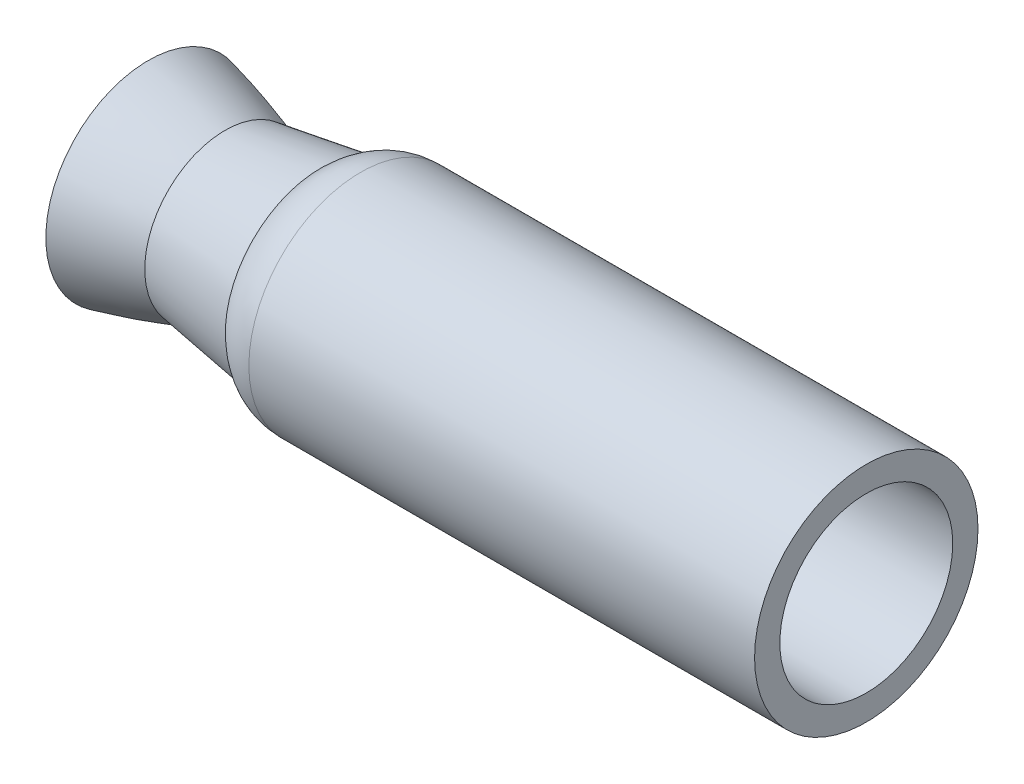
SolidWorks part; units mm, degrees
material "Thornel Mat VMA"
ref_plane "Front Plane" through (0, 0, 0) normal (0, 0, 1) x (1, 0, 0)
ref_plane "Top Plane" through (0, 0, 0) normal (0, 1, 0) x (1, 0, 0)
ref_plane "Right Plane" through (0, 0, 0) normal (1, 0, 0) x (0, 0, -1)
sketch "Sketch1" plane through (0, 0, 0) normal (0, 0, 1) x (1, 0, 0)
  line L0 (189.133, 27.386) -> (28.9492, 27.386)
  line L1 (21.8782, 24.4571) -> (13.5417, 16.1206)
  line L3 (0, 0) -> (-234.9488, 0) construction
  line L5 (16.2213, 30.1139) -> (-13.9816, 25.4377)
  line L8 (189.133, 35.386) -> (28.9492, 35.386)
  line L12 (16.2213, 30.1139) -> (7.8848, 21.7775)
  line L13 (189.133, 27.386) -> (189.133, 35.386)
  line L14 (-40.127, 24.64) -> (-38.315, 32.4321)
  arc A0 (28.9492, 27.386) -> (21.8782, 24.4571) centre (28.9492, 17.386) ccw
  arc A4 (28.9492, 35.386) -> (16.2213, 30.1139) centre (28.9492, 17.386) ccw
  arc A7 (2.3482, 19.2268) -> (2.3482, 19.2268) centre (2.3482, 19.2268) cw
  arc A8 (7.8848, 21.7775) -> (2.3482, 19.2268) centre (1.6623, 28) cw construction
  arc A9 (2.3482, 19.2268) -> (7.8848, 21.7775) centre (1.6623, 28) ccw
  arc A10 (0.1069, 11.2722) -> (0, 11.5361) centre (3.1693, 12.6659) cw construction
  arc A11 (13.5417, 16.1206) -> (0.1069, 11.2722) centre (1.6623, 28) cw construction
  arc A12 (13.5417, 16.1206) -> (1.6623, 11.2) centre (1.6623, 28) cw
  arc A13 (1.6623, 11.2) -> (0, 11.5361) centre (1.6623, 15.4784) cw
  spline S0 degree 2 poles (0, 11.5361) (-19.9483, 19.9476) (-40.127, 24.64) knots 0 0 0 1 1 1 construction
  spline S1 degree 1 poles (2.3482, 19.2268) (-38.315, 32.4321) knots 0 0 1 1 construction
  spline S2 degree 2 poles (0, 11.5361) (-19.9483, 19.9476) (-40.127, 24.64) knots 0 0 0 1 1 1
  spline S3 degree 2 poles (2.3482, 19.2268) (0.3135, 20.0775) (-5.8003, 22.5182) (-13.9784, 25.475) (-28.1602, 30.0701) (-38.315, 32.4321) knots 0.018494 0.018494 0.018494 0.117488 0.315475 0.513463 1 1 1
  dimension "D1" = 10
  dimension "D4" = 16.8
  dimension "D5" = 4.2784
  dimension "D14" = 27.386
  dimension "D16" = 167.2548
  dimension "D2" = 11.2
  dimension "D6" = 45
  dimension "D7" = 24.64
  dimension "D3" = 8
revolve "Revolve1" add sketch "Sketch1" angle 360 about L3
ref_plane "Plane1" through (0, 0, 40) normal (0, 0, 1) x (1, 0, 0)
sketch "Sketch2" plane through (0, 0, 40) normal (0, 0, 1) x (1, 0, 0)
  line L0 (-13.9816, 25.4377) -> (-13.9816, -25.4377) construction
  line L2 (16.2213, -30.1139) -> (16.2213, 30.1139) construction
  line L3 (-13.9816, 25.4377) -> (-13.9816, -25.4377) construction
  line L4 (-13.9816, 0) -> (16.2213, 0) construction
  line L6 (1.6623, 11.2) -> (1.6623, -11.2) construction
  circle A0 centre (1.6623, 0) radius 2.5
  dimension "D2" = 5
sketch "Sketch3" plane through (0, 0, 0) normal (0, 0, 1) x (1, 0, 0)
  line L0 (16.2213, 30.1139) -> (7.8848, 21.7775) construction
  line L1 (16.2213, 30.1139) -> (7.8848, 21.7775)
  line L2 (9.8782, 23.7708) -> (9.8782, 41.25)
  line L3 (9.8782, 41.25) -> (49.8782, 41.25)
  line L4 (49.8782, 41.25) -> (49.8782, 35.386)
  line L5 (189.133, 35.386) -> (28.9492, 35.386) construction
  line L6 (200000, 0) -> (-200234.9488, 0) construction
  line L7 (28.9492, 35.386) -> (28.9492, -35.386) construction
  line L8 (28.9492, 35.386) -> (28.9492, -35.386)
  line L9 (189.133, 35.386) -> (28.9492, 35.386)
  line L10 (21.8782, 24.4571) -> (21.8782, -24.4571) construction
  line L11 (21.8782, 24.4571) -> (21.8782, -24.4571)
  arc A0 (2.3482, 19.2268) -> (7.8848, 21.7775) centre (1.6623, 28) ccw construction
  arc A1 (2.3482, 19.2268) -> (7.8848, 21.7775) centre (1.6623, 28) ccw
  arc A2 (28.9492, 35.386) -> (16.2213, 30.1139) centre (28.9492, 17.386) ccw construction
  arc A3 (28.9492, 35.386) -> (16.2213, 30.1139) centre (28.9492, 17.386) ccw
  spline S0 degree 2 poles (688.9163, -1836.1468) (411.4133, -144.0397) (-5.8003, 22.5182) (-13.9784, 25.475) (-484.9314, 178.0717) (-1112.4109, -1610.0203) knots -19.950852 -19.950852 -19.950852 0.117488 0.315475 0.513463 23.047357 23.047357 23.047357 only from (2.3482, 19.2268) to (-38.315, 32.4321) construction
  spline S1 degree 2 poles (2.3482, 19.2268) (0.3135, 20.0775) (-5.8003, 22.5182) (-13.9784, 25.475) (-28.1602, 30.0701) (-38.315, 32.4321) knots 0.018494 0.018494 0.018494 0.117488 0.315475 0.513463 1 1 1
  dimension "D1" = 40
  dimension "D2" = 41.25
  dimension "D3" = 12
equation "\"theta_t\"= 36.9009 - ( 426.271 / ( \"Aet\" + 7.00037 ) ) + ( 10026.8 / ( \"Aet\" + 7.00037 ) ^ 2 ) - ( 175410 / ( \"Aet\" + 7.00037 ) ^ 3 ) + ( ( 1.6742 * ( 10 ^ 6 ) ) / ( \"Aet\" + 7.00037 ) ^ 4 ) - ( ( 6.7643 * ( 10 ^ 6 ) ) / ( \"Aet\" + 7.00037 ) ^ 5 )"
equation "\"rt\"= 11.2"
equation "\"re\"= sqr ( \"rt\" ^ 2 * \"Aet\" )"
equation "\"Aet\"= 4.84"
equation "\"L\"= 0.8 * ( ( \"re\" / tan ( 15 ) ) - ( \"rt\" / tan ( 15 ) ) )"
equation "\"lc\"= ( \"l*\" / \"cr\" )"
equation "\"b\"= tan ( \"theta_t\" )"
equation "\"a\"= ( \"re\" - \"b\" * \"L\" - \"c\" ) / \"L\" ^ 2"
equation "\"c\"= \"rt\" * ( 1.382 - 0.382 * cos ( \"theta_t\" ) )"
equation "\"cr\"= 5.9789"
equation "\"rc\"= sqr ( \"cr\" * ( \"rt\" ^ 2 ) )"
equation "\"D14@Sketch1\"=\"rc\""
equation "\"l*\"= 1000"
equation "\"D16@Sketch1\"=\"lc\""
equation "\"th\"= 8"
equation "\"theta_cr\"= 45deg"
equation "\"theta_e\"= 5.48 + ( 134.316 / ( \"Aet\" + 1.49269 ) ) - ( 1742.02 / ( \"Aet\" + 1.49269 ) ^ 2 ) + ( 13091 / ( \"Aet\" + 1.49269 ) ^ 3 ) - ( 41929.9 / ( \"Aet\" + 1.49269 ) ^ 4 ) + ( 44445.1 / ( \"Aet\" + 1.49269 ) ^ 5 )"
equation "\"Nx\"= 0"
equation "\"Ny\"= \"c\""
equation "\"Qx\"= ( \"re\" - ( tan ( \"theta_e\" ) * \"L\" ) - \"c\" ) / ( tan ( \"theta_t\" ) - tan ( \"theta_e\" ) )"
equation "\"Qy\"= tan ( \"theta_t\" ) * \"Qx\" + \"c\""
equation "\"Ex\"= \"L\""
equation "\"Ey\"= \"re\""
equation "\"D3@Sketch1\"=\"th\""
equation "\"D2@Sketch1\"=\"rt\""
equation "\"D4@Sketch1\"=\"rt\"*1.5"
equation "\"D5@Sketch1\"=\"rt\"*0.382"
equation "\"D6@Sketch1\"=\"theta_cr\""
equation "\"D7@Sketch1\"=\"re\""
equation "\"D2@Sketch3\"=(88.9)/2 -3.2"
